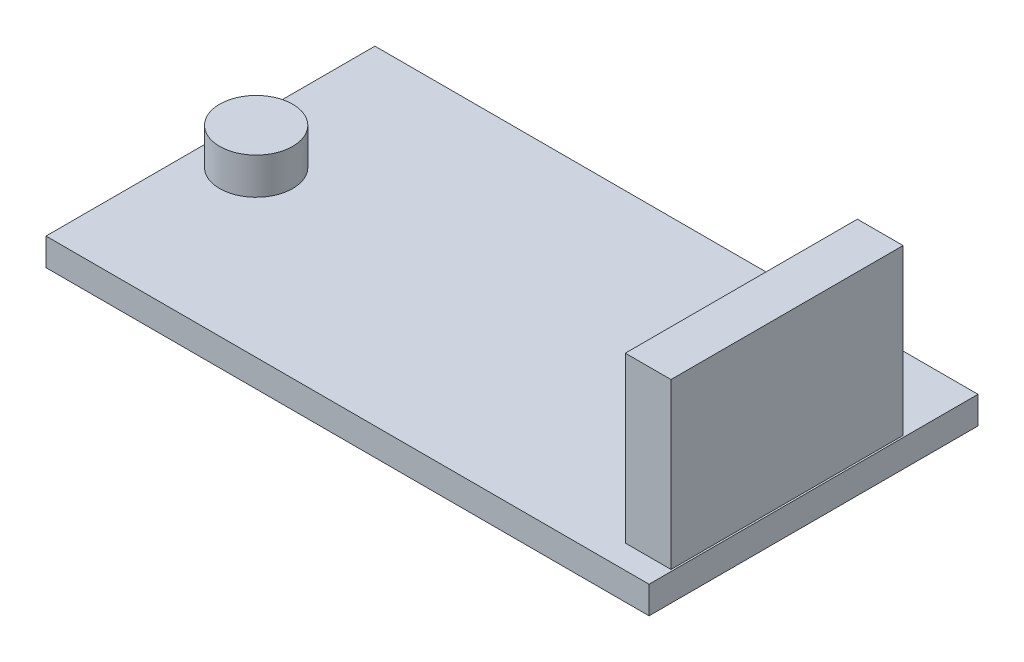
SolidWorks part; units mm, degrees
ref_plane "Front Plane" through (0, 0, 0) normal (0, 0, 1) x (1, 0, 0)
ref_plane "Top Plane" through (0, 0, 0) normal (0, 1, 0) x (1, 0, 0)
ref_plane "Right Plane" through (0, 0, 0) normal (1, 0, 0) x (0, 0, -1)
sketch "Sketch1" plane through (0, 0, 0) normal (0, 1, 0) x (1, 0, 0)
  line L1 (-16.5, 9) -> (16.5, 9)
  line L2 (-16.5, 9) -> (-16.5, -9)
  line L3 (-16.5, -9) -> (16.5, -9)
  line L4 (16.5, 9) -> (16.5, -9)
  line L5 (-16.5, 9) -> (16.5, -9) construction
  line L6 (-16.5, -9) -> (16.5, 9) construction
  point P0 (0, 0)
  dimension "D1" = 18
  dimension "D2" = 33
extrude "Boss-Extrude1" add sketch "Sketch1" along normal blind 1.5
sketch "Sketch2" plane through (0, 1.5, 0) normal (0, 1, 0) x (1, 0, 0)
  line L0 (15.15, -7.7) -> (15.15, -9) construction
  line L1 (16.4, -7.7) -> (13.9, -7.7)
  line L2 (16.4, -7.7) -> (16.4, 5)
  line L3 (16.4, 5) -> (13.9, 5)
  line L4 (13.9, -7.7) -> (13.9, 5)
  line L5 (-16.5, -9) -> (16.5, -9) construction
  line L6 (15.15, 5) -> (15.15, 9) construction
  line L7 (16.5, 9) -> (-16.5, 9) construction
  line L8 (16.4, -1.35) -> (16.5, -1.35) construction
  line L9 (16.5, -9) -> (16.5, 9) construction
  line L10 (13.9, -7.7) -> (16.5, -7.7) construction
  dimension "D1" = 4
  dimension "D2" = 1.3
  dimension "D3" = 0.1
  dimension "D4" = 2.6
extrude "Boss-Extrude2" add sketch "Sketch2" along normal blind 9
sketch "Sketch3" plane through (0, 1.5, 0) normal (0, 1, 0) x (1, 0, 0)
  line L0 (-16.5, 0) -> (-14, 0) construction
  line L1 (-16.5, 9) -> (-16.5, -9) construction
  circle A0 centre (-14, 0) radius 2
  dimension "D2" = 4
  dimension "D1" = 2.5
extrude "Boss-Extrude3" add sketch "Sketch3" along normal blind 2
